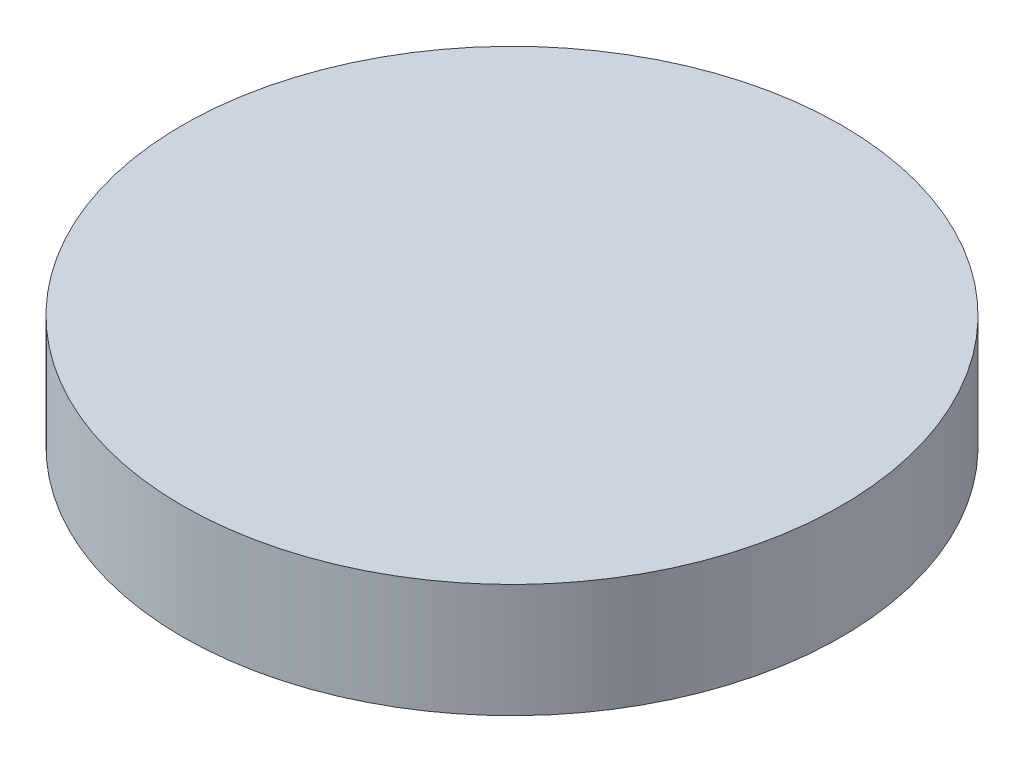
SolidWorks part; units mm, degrees
ref_plane "前视基准面" through (0, 0, 0) normal (0, 0, 1) x (1, 0, 0)
ref_plane "上视基准面" through (0, 0, 0) normal (0, 1, 0) x (1, 0, 0)
ref_plane "右视基准面" through (0, 0, 0) normal (1, 0, 0) x (0, 0, -1)
sketch "草图1" plane through (0, 0, 0) normal (0, 1, 0) x (1, 0, 0)
  circle A0 centre (0, 0) radius 145
  dimension "D1" = 290
extrude "凸台-拉伸1" add sketch "草图1" along normal blind 50
sketch "草图2" plane through (0, 50, 0) normal (0, 1, 0) x (1, 0, 0)
  circle A0 centre (0, 0) radius 38.8 construction
  circle A1 centre (-38.8, 0) radius 7.5
  circle A2 centre (-27.4357, 27.4357) radius 7.5
  circle A3 centre (0, 38.8) radius 7.5
  circle A4 centre (27.4357, 27.4357) radius 7.5
  circle A5 centre (38.8, 0) radius 7.5
  circle A6 centre (27.4357, -27.4357) radius 7.5
  circle A7 centre (0, -38.8) radius 7.5
  circle A8 centre (-27.4357, -27.4357) radius 7.5
  dimension "D1" = 15
  dimension "D2" = 77.6
  dimension "D3" = 8
extrude "切除-拉伸1" [suppressed] cut sketch "草图2" against normal up to next
